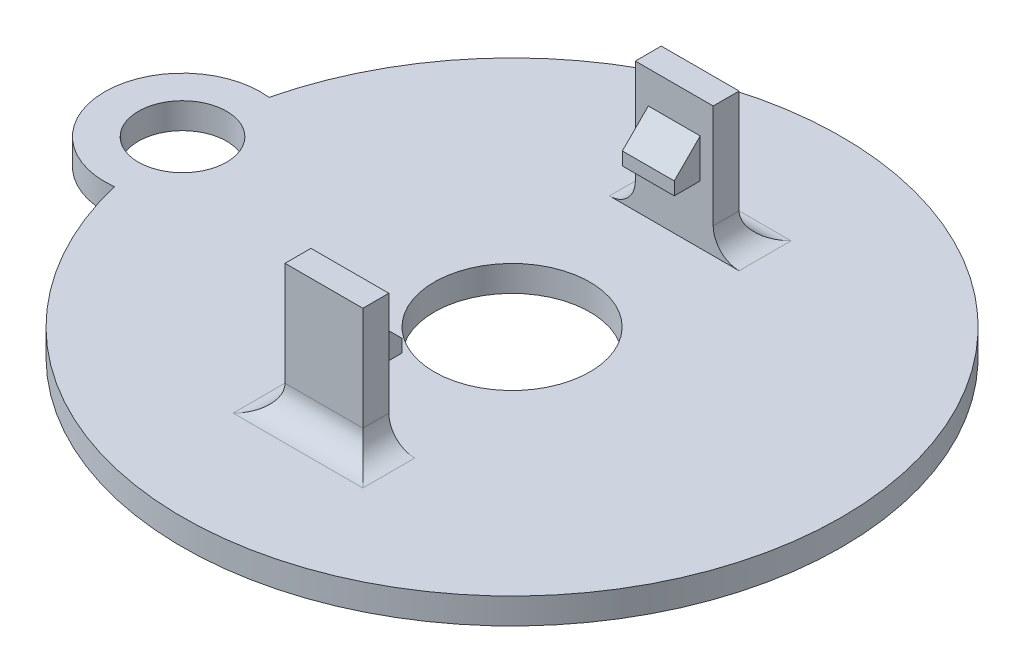
SolidWorks part; units mm, degrees
ref_plane "Front Plane" through (0, 0, 0) normal (0, 0, 1) x (1, 0, 0)
ref_plane "Top Plane" through (0, 0, 0) normal (0, 1, 0) x (1, 0, 0)
ref_plane "Right Plane" through (0, 0, 0) normal (1, 0, 0) x (0, 0, -1)
sketch "Sketch2" plane through (0, 0, 0) normal (0, 1, 0) x (1, 0, 0)
  arc A0 (-12.3457, -2.979) -> (-12.3457, 2.979) centre (0, 0) ccw
  circle A1 centre (0, 0) radius 3
  arc A2 (-12.3457, 2.979) -> (-12.3457, -2.979) centre (-12.7, 0) ccw
  circle A3 centre (-12.7, 0) radius 1.7
  dimension "D1" = 6
  dimension "D2" = 3.4
  dimension "D4" = 6
  dimension "D3" = 12.7
extrude "Boss-Extrude1" add sketch "Sketch2" along normal blind 1
sketch "Sketch3" plane through (0, 1, 0) normal (0, 1, 0) x (1, 0, 0)
  line L0 (0, 0) -> (3, 0) construction
  line L1 (-1.5, 7.25) -> (1.5, 7.25)
  line L2 (-1.5, 7.25) -> (-1.5, 6.25)
  line L3 (-1.5, 6.25) -> (1.5, 6.25)
  line L4 (1.5, 7.25) -> (1.5, 6.25)
  line L6 (-1.5, -6.25) -> (1.5, -6.25)
  line L7 (-1.5, -6.25) -> (-1.5, -7.25)
  line L8 (-1.5, -7.25) -> (1.5, -7.25)
  line L9 (1.5, -6.25) -> (1.5, -7.25)
  point P11 (1.2533, 6.8928)
  point P12 (0, 6.25)
  point P13 (0, -6.25)
  point P14 (2.0129, -7.1207)
  dimension "D1" = 3
  dimension "D2" = 1
  dimension "D3" = 6.25
extrude "Boss-Extrude2" add sketch "Sketch3" along normal blind 5
sketch "Sketch4" plane through (0, 0, 0) normal (1, 0, 0) x (0, 0, -1)
  line L0 (-6.25, 4.75) -> (-5.25, 3.75)
  line L1 (-6.25, 6) -> (-6.25, 1) construction
  line L3 (-6.25, 3.25) -> (-6.25, 4.75)
  line L5 (6.25, 6) -> (6.25, 1) construction
  line L6 (5.25, 3.75) -> (6.25, 4.75)
  line L7 (6.25, 4.75) -> (6.25, 3.25)
  line L8 (-6.25, 3.25) -> (-5.25, 3.25)
  line L9 (-5.25, 3.25) -> (-5.25, 3.75)
  line L10 (5.25, 3.75) -> (5.25, 3.25)
  line L11 (5.25, 3.25) -> (6.25, 3.25)
  line L12 (-7.25, 6) -> (-6.25, 6) construction
  point P9 (-5.0571, 3.1227)
  dimension "D1" = 1.25
  dimension "D2" = 1
  dimension "D3" = 0.5
  dimension "D4" = 1.5
extrude "Boss-Extrude3" add sketch "Sketch4" along normal blind 1 and the other way blind 1
fillet "Fillet1" radius 1 6 edges at (-1.5, 1, -6.75) (-1.5, 1, 6.75) (1.5, 1, 6.75) (1.5, 1, -6.75) (0, 1, -7.25) (0, 1, 7.25)
